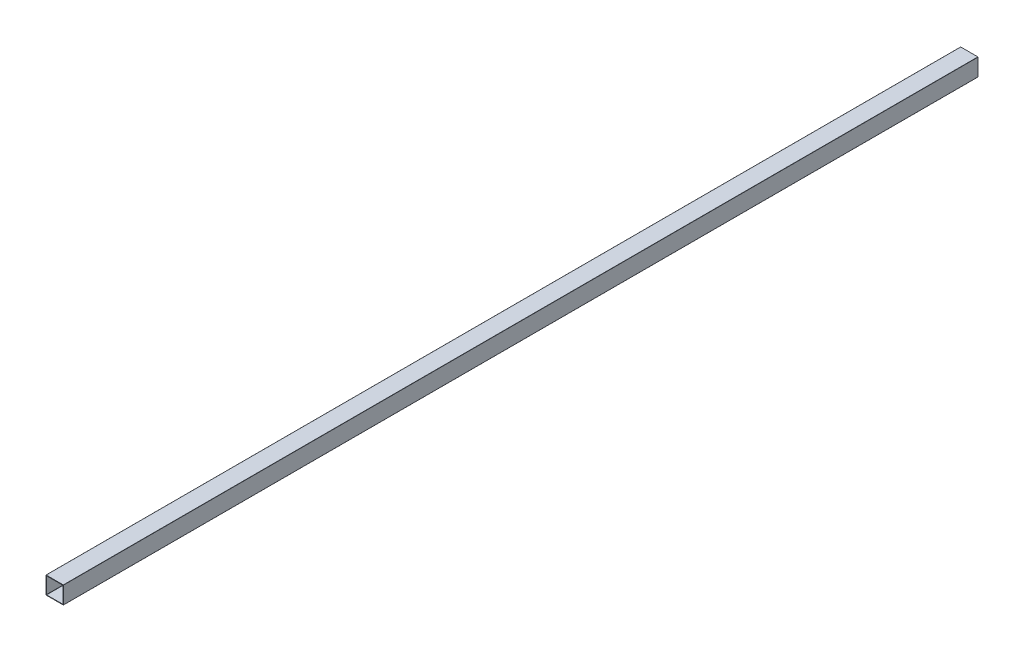
SolidWorks part; units mm, degrees
material "AISI 1035 Acero (SS)"
ref_plane "Alzado" through (0, 0, 0) normal (0, 0, 1) x (1, 0, 0)
ref_plane "Planta" through (0, 0, 0) normal (0, 1, 0) x (1, 0, 0)
ref_plane "Vista lateral" through (0, 0, 0) normal (1, 0, 0) x (0, 0, -1)
sketch "Croquis1" plane through (0, 0, 0) normal (0, 0, 1) x (1, 0, 0)
  line L0 (-54.11, -54.11) -> (-54.11, 54.11)
  line L1 (-57.15, -57.15) -> (57.15, -57.15)
  line L2 (-57.15, -57.15) -> (-57.15, 57.15)
  line L3 (-57.15, 57.15) -> (57.15, 57.15)
  line L4 (57.15, -57.15) -> (57.15, 57.15)
  line L5 (-57.15, -57.15) -> (57.15, 57.15) construction
  line L6 (-57.15, 57.15) -> (57.15, -57.15) construction
  line L7 (-54.11, 54.11) -> (54.11, 54.11)
  line L8 (54.11, -54.11) -> (54.11, 54.11)
  line L9 (-54.11, -54.11) -> (54.11, -54.11)
  point P0 (0, 0)
  dimension "D2" = 114.3
  dimension "D3" = 3.04
extrude "Saliente-Extruir1" add sketch "Croquis1" against normal blind 6000
fillet "Redondeo1" radius 1 8 edges at (-54.11, 54.11, -3000) (54.11, 54.11, -3000) (54.11, -54.11, -3000) (-57.15, -57.15, -3000) (-57.15, 57.15, -3000) (-54.11, -54.11, -3000) (57.15, -57.15, -3000) (57.15, 57.15, -3000)
